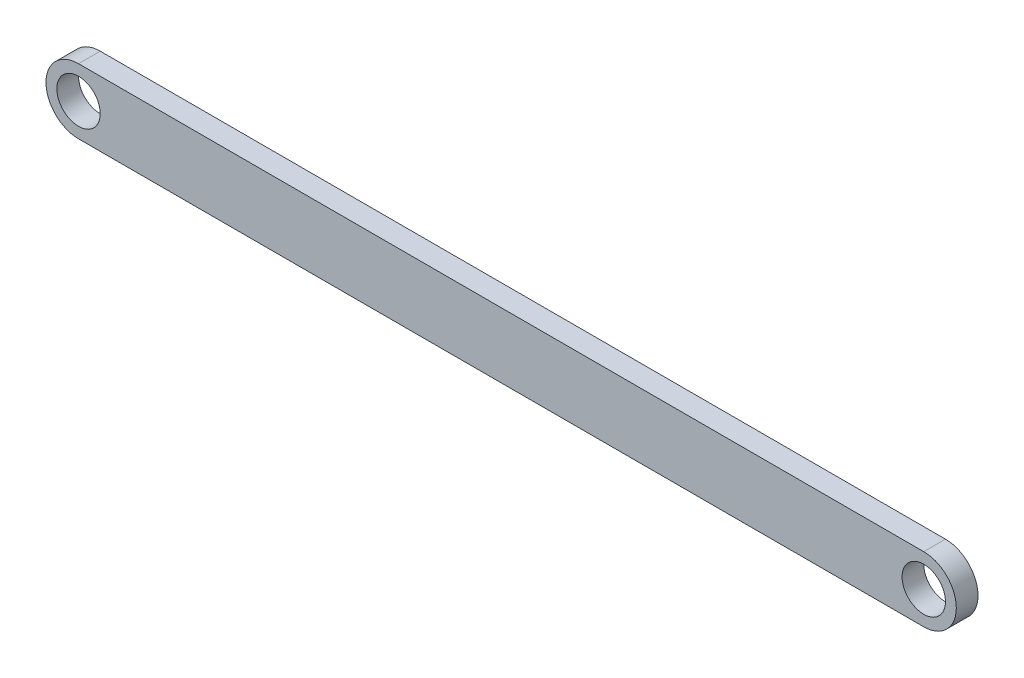
SolidWorks part; units mm, degrees
ref_plane "Front Plane" through (0, 0, 0) normal (0, 0, 1) x (1, 0, 0)
ref_plane "Top Plane" through (0, 0, 0) normal (0, 1, 0) x (1, 0, 0)
ref_plane "Right Plane" through (0, 0, 0) normal (1, 0, 0) x (0, 0, -1)
sketch "Sketch1" plane through (0, 0, 0) normal (0, 0, 1) x (1, 0, 0)
  line L0 (0, 0) -> (-38.95, 0) construction
  line L1 (0, -1.5) -> (-38.95, -1.5)
  line L2 (0, 1.5) -> (-38.95, 1.5)
  arc A0 (0, -1.5) -> (0, 1.5) centre (0, 0) ccw
  arc A1 (-38.95, 1.5) -> (-38.95, -1.5) centre (-38.95, 0) ccw
  circle A2 centre (-38.95, 0) radius 1
  circle A3 centre (0, 0) radius 1
  point P3 (-19.475, 0)
  dimension "D1" = 2
  dimension "D3" = 2
  dimension "D4" = 1.5
  dimension "D2" = 38.95
extrude "Boss-Extrude1" add sketch "Sketch1" along normal mid plane 1
